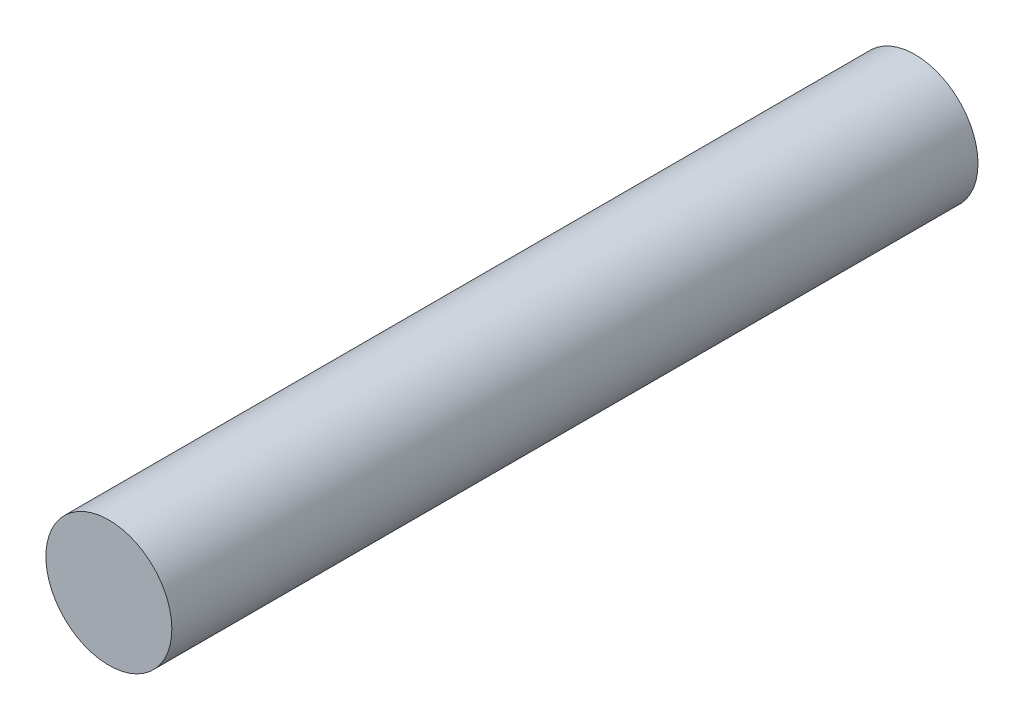
SolidWorks part; units mm, degrees
ref_plane "Front" through (0, 0, 0) normal (0, 0, 1) x (1, 0, 0)
ref_plane "Top" through (0, 0, 0) normal (0, 1, 0) x (1, 0, 0)
ref_plane "Right" through (0, 0, 0) normal (1, 0, 0) x (0, 0, -1)
sketch "Esquisse1" plane through (0, 0, 0) normal (0, 0, 1) x (1, 0, 0)
  circle A0 centre (0, 0) radius 2.5
  dimension "D1" = 5
extrude "Boss-Extrude1" add sketch "Esquisse1" along normal mid plane 32
